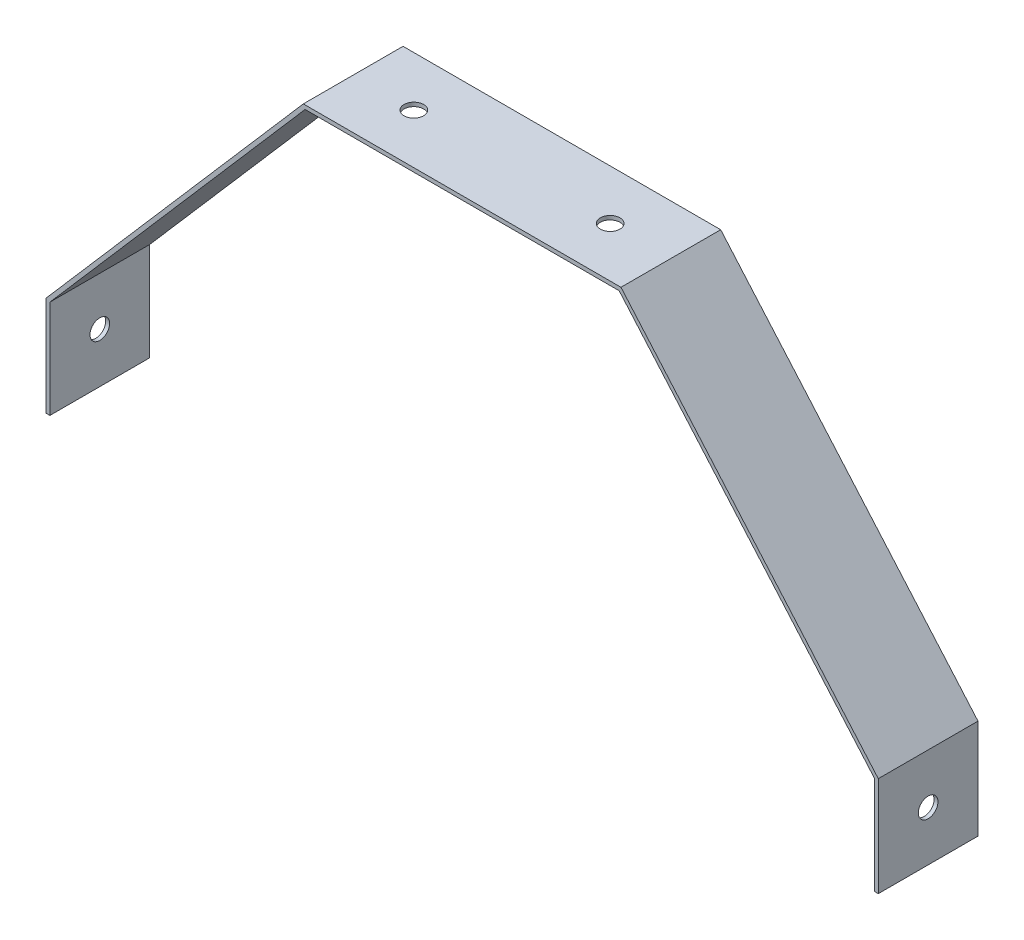
SolidWorks part; units mm, degrees
material "1060 Alloy"
ref_plane "Front Plane" through (0, 0, 0) normal (0, 0, 1) x (1, 0, 0)
ref_plane "Top Plane" through (0, 0, 0) normal (0, 1, 0) x (1, 0, 0)
ref_plane "Right Plane" through (0, 0, 0) normal (1, 0, 0) x (0, 0, -1)
sketch "Sketch2" plane through (0, 0, 0) normal (0, 0, 1) x (1, 0, 0)
  line L0 (-40, 0) -> (40, 0)
  line L1 (0, 0) -> (0, -100) construction
  line L2 (-105, -100) -> (105, -100) construction
  line L5 (-105, -75) -> (-40, 0)
  line L6 (-105, -100) -> (105, -100) construction
  line L7 (-105, -100) -> (-105, -75)
  line L8 (-105, -75) -> (105, -75) construction
  line L9 (105, -100) -> (105, -75)
  line L10 (40, 0) -> (105, -75)
  point P4 (0, 0)
  point P10 (0, -100)
  dimension "D1" = 80
  dimension "D2" = 100
  dimension "D3" = 105
  dimension "D4" = 25
  dimension "D5" = 210
extrude "Extrude-Thin1" add sketch "Sketch2" along normal blind 25.4 thin thin type one direction wall 1
sketch "Sketch3" plane through (0, 1, 0) normal (0, 1, 0) x (1, 0, 0)
  line L0 (-25, -12.7) -> (25, -12.7)
  circle A0 centre (-25, -12.7) radius 2.5
  circle A1 centre (25, -12.7) radius 2.5
  point P3 (0, -12.7)
  dimension "D1" = 5
  dimension "D2" = 5
  dimension "D3" = 12.7
extrude "Cut-Extrude1" cut sketch "Sketch3" against normal blind 10
sketch "Sketch4" plane through (0, 0, 0) normal (1, 0, 0) x (0, 0, -1)
  line L0 (-25.4, -74.627) -> (0, -100) construction
  circle A0 centre (-12.7, -87.3135) radius 2.5
  dimension "D1" = 5
extrude "Cut-Extrude2" cut sketch "Sketch4" against normal through all both and the other way through all contours A0
